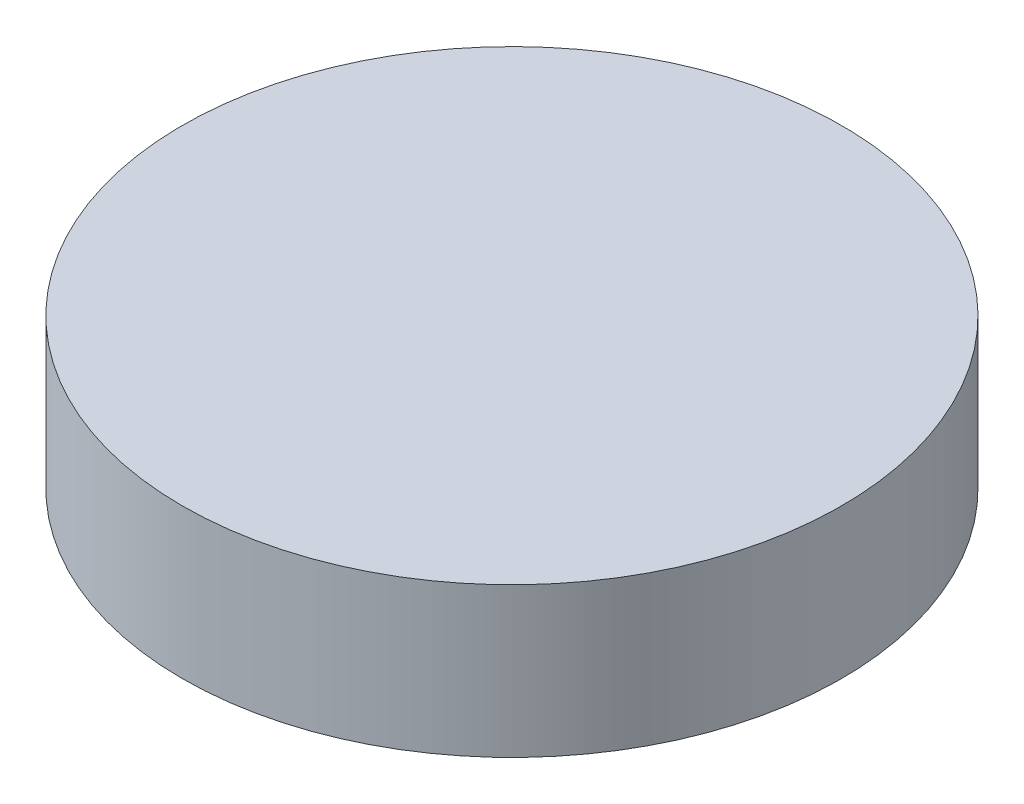
SolidWorks part; units mm, degrees
ref_plane "Front Plane" through (0, 0, 0) normal (0, 0, 1) x (1, 0, 0)
ref_plane "Top Plane" through (0, 0, 0) normal (0, 1, 0) x (1, 0, 0)
ref_plane "Right Plane" through (0, 0, 0) normal (1, 0, 0) x (0, 0, -1)
sketch "Sketch1" plane through (0, 0, 0) normal (0, 1, 0) x (1, 0, 0)
  circle A0 centre (0, 0) radius 55.9594
  dimension "D1" = 111.9188
extrude "Boss-Extrude1" add sketch "Sketch1" along normal blind 25.4
